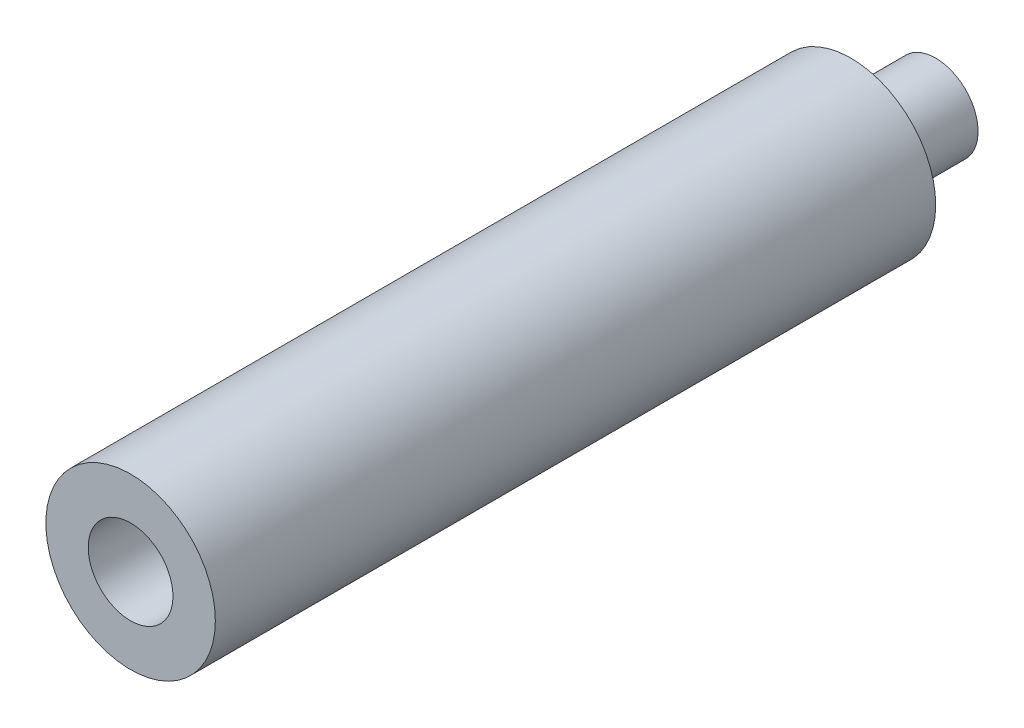
SolidWorks part; units mm, degrees
ref_plane "정면" through (0, 0, 0) normal (0, 0, 1) x (1, 0, 0)
ref_plane "윗면" through (0, 0, 0) normal (0, 1, 0) x (1, 0, 0)
ref_plane "우측면" through (0, 0, 0) normal (1, 0, 0) x (0, 0, -1)
sketch "스케치1" plane through (0, 0, 0) normal (0, 0, 1) x (1, 0, 0)
  circle A0 centre (0, 0) radius 20
  dimension "D1" = 40
extrude "보스-돌출1" add sketch "스케치1" along normal blind 170
sketch "스케치2" plane through (0, 0, 0) normal (0, 0, -1) x (-1, 0, 0)
  circle A0 centre (0, 0) radius 10
  dimension "D1" = 20
extrude "보스-돌출2" add sketch "스케치2" along normal blind 20
sketch "스케치3" plane through (0, 0, 170) normal (0, 0, 1) x (1, 0, 0)
  circle A0 centre (0, 0) radius 10
  dimension "D1" = 20
extrude "컷-돌출1" cut sketch "스케치3" against normal blind 20
